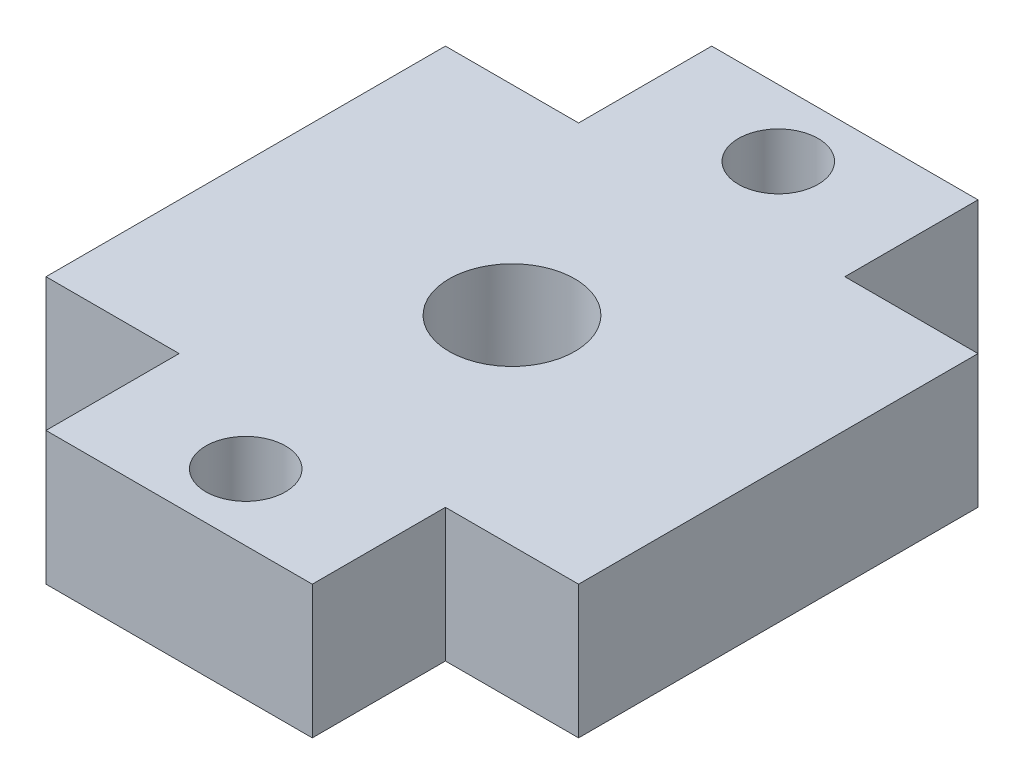
SolidWorks part; units mm, degrees
material "Beech"
ref_plane "Front Plane" through (0, 0, 0) normal (0, 0, 1) x (1, 0, 0)
ref_plane "Top Plane" through (0, 0, 0) normal (0, 1, 0) x (1, 0, 0)
ref_plane "Right Plane" through (0, 0, 0) normal (1, 0, 0) x (0, 0, -1)
sketch "Sketch1" plane through (0, 0, 0) normal (0, 1, 0) x (1, 0, 0)
  line L1 (-12.7, -15.875) -> (12.7, -15.875)
  line L2 (-12.7, -15.875) -> (-12.7, 15.875)
  line L3 (-12.7, 15.875) -> (12.7, 15.875)
  line L4 (12.7, -15.875) -> (12.7, 15.875)
  line L5 (-12.7, -15.875) -> (12.7, 15.875) construction
  line L6 (-12.7, 15.875) -> (12.7, -15.875) construction
  point P0 (0, 0)
  dimension "D1" = 25.4
  dimension "D2" = 31.75
extrude "Boss-Extrude1" add sketch "Sketch1" along normal mid plane 6.35
sketch "Sketch2" plane through (0, 3.175, 0) normal (0, 1, 0) x (1, 0, 0)
  line L0 (0, 0) -> (0, 15.875) construction
  line L1 (-12.7, 15.875) -> (-6.35, 15.875)
  line L2 (-12.7, 15.875) -> (-12.7, 9.525)
  line L3 (-12.7, 9.525) -> (-6.35, 9.525)
  line L4 (-6.35, 15.875) -> (-6.35, 9.525)
  line L5 (12.7, 15.875) -> (-12.7, 15.875) construction
  dimension "D1" = 6.35
  dimension "D2" = 6.35
extrude "Cut-Extrude1" cut sketch "Sketch2" against normal up to next
mirror "Mirror1" about plane through (0, 0, 0) normal (0, 0, 1) of "Cut-Extrude1"
mirror "Mirror2" about plane through (0, 0, 0) normal (1, 0, 0) of "Mirror1", "Cut-Extrude1"
hole_wizard "#6 Clearance Hole1" positions "Sketch4" profile "Sketch3" hole size "#6" standard "ANSI Inch"
sketch "Sketch4" plane through (0, 3.175, 0) normal (0, 1, 0) x (1, 0, 0)
  line L0 (0, 0) -> (0, 15.875) construction
  line L1 (6.35, 15.875) -> (-6.35, 15.875) construction
  line L2 (0, 15.875) -> (-6.35, 12.7) construction
  line L3 (-6.35, 9.525) -> (-6.35, 15.875) construction
  line L4 (-6.35, 12.7) -> (6.35, 12.7) construction
  line L5 (6.35, 9.525) -> (6.35, 15.875) construction
  point P17 (0, 12.7)
sketch "Sketch3" plane through (0, 3.175, -12.7) normal (1, 0, 0) x (0, 0, 1)
  line L0 (0, 0) -> (0, 7.4908)
  line L1 (0, 7.4908) -> (1.8986, 6.35)
  line L2 (1.8986, 6.35) -> (1.8986, 0)
  line L5 (1.8986, 0) -> (0, 0)
  line L10 (0, 7.4908) -> (-1.8986, 6.35) construction
  line L11 (0, -6.35) -> (0, 107.95) construction
  dimension "Hole Dia." = 3.7973
  dimension "Hole Depth" = 6.35
  dimension "Drill Angle" = 118
mirror "Mirror3" about plane through (0, 0, 0) normal (0, 0, 1) of "#6 Clearance Hole1"
sketch "Sketch5" plane through (0, 3.175, 0) normal (0, 1, 0) x (1, 0, 0)
  line L0 (0, 15.875) -> (0, -15.875) construction
  line L1 (6.35, 15.875) -> (-6.35, 15.875) construction
  line L2 (-6.35, -15.875) -> (6.35, -15.875) construction
  line L3 (-12.7, 0) -> (12.7, 0) construction
  line L4 (-12.7, 9.525) -> (-12.7, -9.525) construction
  line L5 (12.7, -9.525) -> (12.7, 9.525) construction
  circle A0 centre (0, 0) radius 3
  dimension "D1" = 6
extrude "Cut-Extrude2" cut sketch "Sketch5" against normal up to next
ref_plane "Plane1" through (0, 0, -12.7) normal (0, 0, -1) x (-1, 0, 0)
ref_plane "Plane2" through (0, 0, 12.7) normal (0, 0, 1) x (1, 0, 0)
